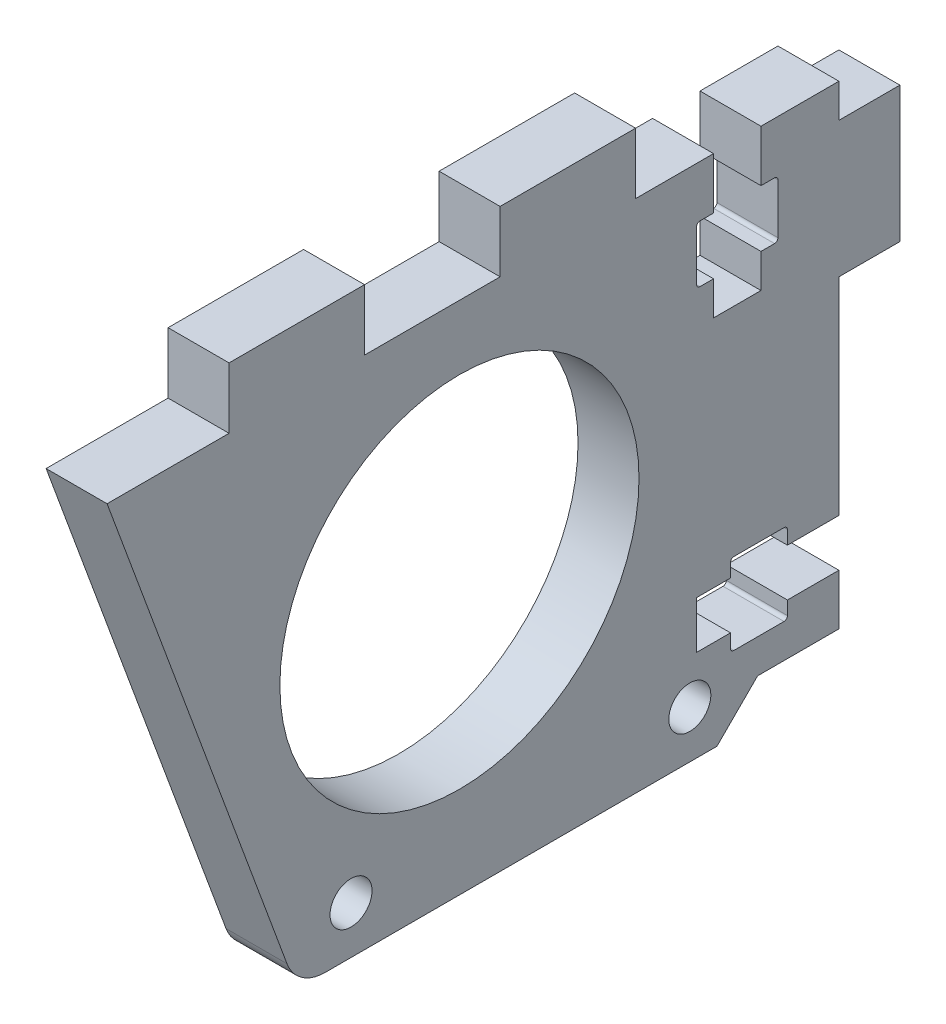
SolidWorks part; units mm, degrees
ref_plane "Front Plane" through (0, 0, 0) normal (0, 0, 1) x (1, 0, 0)
ref_plane "Top Plane" through (0, 0, 0) normal (0, 1, 0) x (1, 0, 0)
ref_plane "Right Plane" through (0, 0, 0) normal (1, 0, 0) x (0, 0, -1)
sketch "Sketch1" plane through (0, 0, 0) normal (1, 0, 0) x (0, 0, -1)
  line L0 (0, 0) -> (0, -35)
  line L1 (0, -35) -> (-54, 0)
  line L2 (-54, 0) -> (0, 0)
  dimension "D1" = 35
  dimension "D2" = 54
extrude "Boss-Extrude1" add sketch "Sketch1" along normal blind 4.5
sketch "Sketch2" plane through (4.5, 0, 0) normal (1, 0, 0) x (0, 0, -1)
  line L0 (0, -35) -> (0, 0) construction
  line L1 (-4.5, -2.5) -> (4.5, -2.5)
  line L2 (-4.5, -2.5) -> (-4.5, -12.5)
  line L3 (-4.5, -12.5) -> (4.5, -12.5)
  line L4 (4.5, -2.5) -> (4.5, -12.5)
  line L5 (-4.5, -2.5) -> (4.5, -12.5) construction
  line L6 (-4.5, -12.5) -> (4.5, -2.5) construction
  line L7 (0, 0) -> (-54, 0) construction
  point P0 (0, -7.5)
  dimension "D1" = 10
  dimension "D2" = 7.5
  dimension "D3" = 4.5
extrude "Boss-Extrude2" add sketch "Sketch2" against normal through all
sketch "Sketch3" plane through (4.5, 0, 0) normal (1, 0, 0) x (0, 0, -1)
  line L0 (0, -35) -> (-15, -35)
  line L1 (0, -25) -> (-54, 0)
  line L4 (0, -35) -> (0, -12.5) construction
  line L5 (0, -25) -> (0, -35)
  line L6 (-54, 0) -> (-15, -35)
  dimension "D1" = 15
  dimension "D2" = 10
extrude "Boss-Extrude3" add sketch "Sketch3" against normal through all
sketch "Sketch4" plane through (4.5, 0, 0) normal (1, 0, 0) x (0, 0, -1)
  line L0 (0, -29.5) -> (-10.5, -29.5) construction
  line L1 (0, -35) -> (0, -12.5) construction
  line L2 (0, -27.75) -> (-10.5, -27.75) construction
  line L3 (-10.5, -27.75) -> (-10.5, -31.25) construction
  line L4 (0, -31.25) -> (0, -27.75)
  line L5 (0, -27.75) -> (-3.8, -27.75)
  line L6 (-3.8, -27.75) -> (-3.8, -26.75)
  line L7 (-4.05, -26.5) -> (-7.75, -26.5)
  line L8 (-8, -26.75) -> (-8, -27.75)
  line L9 (-8, -27.75) -> (-10.5, -27.75)
  line L10 (-10.5, -27.75) -> (-10.5, -31.25)
  line L12 (0, -31.25) -> (-10.5, -31.25) construction
  line L13 (-8, -31.25) -> (-10.5, -31.25)
  line L14 (-8, -32.25) -> (-8, -31.25)
  line L15 (-4.05, -32.5) -> (-7.75, -32.5)
  line L16 (-3.8, -31.25) -> (-3.8, -32.25)
  line L17 (0, -31.25) -> (-3.8, -31.25)
  line L18 (4.5, -12.5) -> (4.5, -2.5) construction
  line L19 (0, -18.5) -> (-33.3857, -18.5) construction
  line L20 (-54, 0) -> (-15, -35) construction
  line L37 (0, -31.25) -> (-10.5, -31.25) construction
  arc A0 (-8, -32.25) -> (-7.75, -32.5) centre (-7.75, -32.25) ccw
  arc A1 (-4.05, -32.5) -> (-3.8, -32.25) centre (-4.05, -32.25) ccw
  arc A2 (-3.8, -26.75) -> (-4.05, -26.5) centre (-4.05, -26.75) ccw
  arc A3 (-7.75, -26.5) -> (-8, -26.75) centre (-7.75, -26.75) ccw
  point P10 (4.5, -7.5)
  point P20 (-8, -32.5)
  point P23 (-3.8, -32.5)
  point P26 (-3.8, -26.5)
  point P29 (-8, -26.5)
  dimension "D7" = 0.25
  dimension "D1" = 10.5
  dimension "D2" = 1.75
  dimension "D3" = 3
  dimension "D4" = 4.2
  dimension "D5" = 8
  dimension "D6" = 22
extrude "Cut-Extrude1" cut sketch "Sketch4" against normal through all
sketch "Sketch5" plane through (4.5, 0, 0) normal (1, 0, 0) x (0, 0, -1)
  line L0 (0, 0) -> (-54, 0) construction
  line L1 (-25, 4.5) -> (-15, 4.5)
  line L2 (-25, 4.5) -> (-25, 0)
  line L3 (0, 0) -> (-54, 0) construction
  line L4 (-15, 4.5) -> (-15, 0)
  line L5 (-25, 4.5) -> (-20, 0) construction
  line L6 (-20, 0) -> (-15, 4.5) construction
  line L7 (-30, 0) -> (-30, 4.5) construction
  line L8 (-40, 0) -> (-45, 4.5) construction
  line L9 (-35, 4.5) -> (-40, 0) construction
  line L10 (-45, 4.5) -> (-45, 0)
  line L12 (-35, 4.5) -> (-35, 0)
  line L13 (-35, 4.5) -> (-45, 4.5)
  line L14 (-20, 0) -> (-15, 4.5) construction
  line L15 (-15, 0) -> (-25, 0)
  line L16 (-35, 0) -> (-45, 0)
  point P0 (-20, 0)
  point P14 (-40, 0)
  dimension "D3" = 4.5
  dimension "D1" = 20
  dimension "D2" = 10
  dimension "D4" = 20
  dimension "D5" = 5
extrude "Boss-Extrude4" add sketch "Sketch5" against normal through all
sketch "Sketch8" [suppressed] plane through (4.5, 0, 0) normal (1, 0, 0) x (0, 0, -1)
  line L0 (-15, -30) -> (-27, -30) construction
  line L1 (-15, -35) -> (-27, -35)
  line L2 (-15, -25) -> (-27, -25)
  line L3 (-15, -35) -> (0, -35) construction
  line L4 (-15, -25) -> (-15, -35)
  arc A1 (-27, -25) -> (-27, -35) centre (-27, -30) ccw
  dimension "D5" = 5
  dimension "D1" = 0
  dimension "D2" = 12
  dimension "D3" = 0
  dimension "D4" = 10
extrude "Boss-Extrude5" [suppressed] add sketch "Sketch8" against normal up to surface (4.5 mm away)
sketch "Sketch9" [suppressed] plane through (4.5, 0, 0) normal (1, 0, 0) x (0, 0, -1)
  line L0 (-27, -30) -> (-22, -30) construction
  line L1 (-27, -27) -> (-22, -27)
  line L2 (-27, -33) -> (-22, -33)
  arc A0 (-27, -27) -> (-27, -33) centre (-27, -30) ccw
  arc A1 (-22, -33) -> (-22, -27) centre (-22, -30) ccw
  point P3 (-24.5, -30)
  dimension "D1" = 3
  dimension "D2" = 5
extrude "Cut-Extrude3" [suppressed] cut sketch "Sketch9" against normal through all
sketch "Sketch10" plane through (0, 0, 0) normal (-1, 0, 0) x (0, 0, 1)
  line L0 (15, -35) -> (54, -12)
  line L1 (54, -12) -> (54, 0)
  line L3 (54, 0) -> (15, -35)
  dimension "D1" = 12
extrude "Boss-Extrude6" [suppressed] add sketch "Sketch10" against normal through all
sketch "Sketch6" plane through (4.5, 0, 0) normal (1, 0, 0) x (0, 0, -1)
  line L0 (-30, 0) -> (-30, -10.5) construction
  line L1 (-25, 0) -> (-35, 0) construction
  line L2 (-28.25, -10.5) -> (-31.75, -10.5) construction
  line L3 (-31.75, -10.5) -> (-31.75, 0) construction
  line L4 (-28.25, 0) -> (-31.75, 0)
  line L5 (-31.75, 0) -> (-31.75, -3.8)
  line L6 (-31.75, -3.8) -> (-32.75, -3.8)
  line L7 (-33, -4.05) -> (-33, -7.75)
  line L8 (-32.75, -8) -> (-31.75, -8)
  line L9 (-31.75, -8) -> (-31.75, -10.5)
  line L10 (-31.75, -10.5) -> (-28.25, -10.5)
  line L11 (-28.25, -10.5) -> (-28.25, 0) construction
  line L12 (-28.25, -8) -> (-28.25, -10.5)
  line L13 (-27.25, -8) -> (-28.25, -8)
  line L14 (-27, -4.05) -> (-27, -7.75)
  line L15 (-28.25, -3.8) -> (-27.25, -3.8)
  line L16 (-28.25, 0) -> (-28.25, -3.8)
  arc A0 (-33, -7.75) -> (-32.75, -8) centre (-32.75, -7.75) ccw
  arc A1 (-32.75, -3.8) -> (-33, -4.05) centre (-32.75, -4.05) ccw
  arc A2 (-27.25, -3.8) -> (-27, -4.05) centre (-27.25, -4.05) cw
  arc A3 (-27, -7.75) -> (-27.25, -8) centre (-27.25, -7.75) cw
  point P12 (-33, -8)
  point P15 (-33, -3.8)
  point P26 (-27, -3.8)
  point P27 (-27, -8)
  dimension "D1" = 10.5
  dimension "D2" = 1.75
  dimension "D4" = 4.2
  dimension "D6" = 0.25
  dimension "D3" = 8
  dimension "D5" = 3
extrude "Cut-Extrude2" [suppressed] cut sketch "Sketch6" against normal through all
sketch "Sketch11" plane through (0, 0, 0) normal (-1, 0, 0) x (0, 0, 1)
  line L0 (7.5, 0) -> (7.5, -10.5) construction
  line L1 (0, 0) -> (15, 0) construction
  line L2 (5.75, -10.5) -> (9.25, -10.5)
  line L3 (9.25, -10.5) -> (9.25, -8)
  line L4 (9.25, -8) -> (10.25, -8)
  line L5 (10.5, -7.75) -> (10.5, -4.05)
  line L6 (10.25, -3.8) -> (9.25, -3.8)
  line L7 (9.25, -3.8) -> (9.25, 0)
  line L8 (9.25, 0) -> (5.75, 0)
  line L9 (9.25, -8) -> (9.25, -3.8) construction
  line L10 (0, 0) -> (15, 0) construction
  line L11 (5.75, -8) -> (5.75, -3.8) construction
  line L12 (5.75, -3.8) -> (5.75, 0)
  line L13 (4.75, -3.8) -> (5.75, -3.8)
  line L14 (4.5, -7.75) -> (4.5, -4.05)
  line L15 (5.75, -8) -> (4.75, -8)
  line L16 (5.75, -10.5) -> (5.75, -8)
  arc A0 (10.5, -4.05) -> (10.25, -3.8) centre (10.25, -4.05) ccw
  arc A1 (4.75, -3.8) -> (4.5, -4.05) centre (4.75, -4.05) ccw
  arc A2 (10.25, -8) -> (10.5, -7.75) centre (10.25, -7.75) ccw
  arc A3 (4.5, -7.75) -> (4.75, -8) centre (4.75, -7.75) ccw
  point P11 (7.5, 0)
  point P22 (10.5, -3.8)
  point P25 (4.5, -3.8)
  point P28 (10.5, -8)
  point P31 (4.5, -8)
  dimension "D7" = 0.25
  dimension "D1" = 10.5
  dimension "D3" = 3
  dimension "D8" = 0.25
  dimension "D2" = 4.2
  dimension "D4" = 8
  dimension "D5" = 1.75
  dimension "D6" = 0
extrude "Cut-Extrude4" cut sketch "Sketch11" against normal through all
sketch "Sketch12" plane through (0, 0, 0) normal (-1, 0, 0) x (0, 0, 1)
  line L0 (28, -18) -> (16, -6) construction
  line L1 (28, -18) -> (28, -4.75) construction
  line L2 (28, -18) -> (40, -6) construction
  line L3 (28, -18) -> (14.75, -18) construction
  line L4 (28, -18) -> (16, -30) construction
  line L5 (28, -18) -> (16, -6) construction
  line L6 (0, -27.75) -> (0, -12.5) construction
  line L7 (25, 0) -> (35, 0) construction
  circle A0 centre (28, -18) radius 13.25
  circle A1 centre (16, -6) radius 1.55
  circle A2 centre (40, -6) radius 1.55
  circle A3 centre (16, -30) radius 1.55
  dimension "D1" = 26.5
  dimension "D2" = 3.1
  dimension "D3" = 12
  dimension "D4" = 45
  dimension "D5" = 28
  dimension "D6" = 18
extrude "Cut-Extrude5" [suppressed] cut sketch "Sketch12" against normal through all
sketch "Sketch13" [suppressed] plane through (0, 0, 0) normal (-1, 0, 0) x (0, 0, 1)
  line L0 (38.894, -10.458) -> (43.005, -7.6119)
  line L1 (19.9513, -28.5252) -> (16.914, -32.497)
  line L6 (28, -18) -> (54, 0) construction
  line L7 (28, -18) -> (15, -35) construction
  arc A0 (19.9513, -28.5252) -> (38.894, -10.458) centre (28, -18) ccw
  arc A1 (16.914, -32.497) -> (43.005, -7.6119) centre (28, -18) ccw
  arc A3 (40.0595, -12.5107) -> (21.2428, -29.3975) centre (28, -18) ccw construction
  dimension "D1" = 5
extrude "Boss-Extrude7" [suppressed] add sketch "Sketch13" against normal through all
sketch "Sketch14" [suppressed] plane through (0, 0, 0) normal (-1, 0, 0) x (0, 0, 1)
  line L0 (28, -4.75) -> (28, -31.25) construction
  line L1 (28, -18) -> (40, -30) construction
  circle A0 centre (28, -18) radius 13.25 construction
  circle A1 centre (40, -30) radius 3.5
  dimension "D2" = 7
  dimension "D1" = 45
  dimension "D3" = 12
extrude "Boss-Extrude8" [suppressed] add sketch "Sketch14" against normal through all
sketch "Sketch15" [suppressed] plane through (0, 0, 0) normal (-1, 0, 0) x (0, 0, 1)
  line L0 (42.4749, -32.4749) -> (28, -18) construction
  arc A0 (38.305, -33.0622) -> (43.0622, -28.305) centre (40, -30) ccw construction
  circle A1 centre (40, -30) radius 1.55
  dimension "D1" = 3.1
extrude "Cut-Extrude6" [suppressed] cut sketch "Sketch15" against normal through all
sketch "Sketch16" plane through (4.5, 0, 0) normal (1, 0, 0) x (0, 0, -1)
  line L0 (0, -34.5) -> (-39, -34.5) construction
  line L1 (0, -27.75) -> (0, -12.5) construction
  line L2 (-15, -34.5) -> (-39, -34.5) construction
  line L3 (-15, -38.5) -> (-39, -38.5)
  line L4 (-15, -30.5) -> (-39, -30.5)
  arc A0 (-15, -38.5) -> (-15, -30.5) centre (-15, -34.5) ccw
  arc A1 (-39, -30.5) -> (-39, -38.5) centre (-39, -34.5) ccw
  point P5 (-27, -34.5)
  point P12 (0, -20.125)
  dimension "D1" = 4
  dimension "D2" = 34.5
  dimension "D3" = 39
  dimension "D4" = 15
extrude "Boss-Extrude9" [suppressed] add sketch "Sketch16" against normal through all
sketch "Sketch17" [suppressed] plane through (4.5, 0, 0) normal (1, 0, 0) x (0, 0, -1)
  line L0 (-43, -34.5) -> (0, -34.5) construction
  line L1 (0, -27.75) -> (0, -12.5) construction
  line L2 (-26.5, -34.5) -> (-26.5, -20.0064) construction
  arc A0 (-42.1823, -32.0766) -> (-39, -38.5) centre (-39, -34.5) ccw construction
  circle A1 centre (-39, -34.5) radius 1.55
  circle A2 centre (-14, -34.5) radius 1.55
  dimension "D1" = 3.1
  dimension "D2" = 12.5
extrude "Cut-Extrude7" [suppressed] cut sketch "Sketch17" against normal through all
sketch "Sketch18" [suppressed] plane through (4.5, 0, 0) normal (1, 0, 0) x (0, 0, -1)
  line L0 (-15, -38.5) -> (0, -35)
  line L1 (0, -35) -> (-11.0314, -35)
  line L2 (-11.0314, -35) -> (-15, -38.5)
extrude "Boss-Extrude10" [suppressed] add sketch "Sketch18" against normal through all
sketch "Sketch20" plane through (4.5, 0, 0) normal (1, 0, 0) x (0, 0, -1)
  line L0 (0, -35) -> (0, -31.25) construction
  line L1 (-9, -38) -> (-37.9081, -38)
  line L2 (-40.7232, -36.0371) -> (-54, 0)
  line L3 (-54, 0) -> (-15, -35)
  line L4 (-15, -35) -> (-6, -35)
  line L5 (-9, -38) -> (-6, -35)
  line L6 (-40.7232, -36.0371) -> (-40, -38) construction
  line L7 (-40, -38) -> (-37.9081, -38) construction
  arc A1 (-37.9081, -38) -> (-40.7232, -36.0371) centre (-37.9081, -35) cw
  point P0 (0, -33.125)
  point P14 (-40, -38)
  dimension "D3" = 6
  dimension "D4" = 3
  dimension "D1" = 40
  dimension "D2" = 3
  dimension "D5" = 135
extrude "Boss-Extrude11" add sketch "Sketch20" against normal through all
sketch "Sketch21" plane through (4.5, 0, 0) normal (1, 0, 0) x (0, 0, -1)
  line L0 (0, -34.5) -> (-41.2895, -34.5) construction
  line L1 (0, -35) -> (0, -31.25) construction
  line L2 (-54, 0) -> (-40.7232, -36.0371) construction
  line L3 (0, -27.75) -> (0, -12.5) construction
  circle A0 centre (-36, -34.5) radius 1.55
  circle A1 centre (-11, -34.5) radius 1.55
  dimension "D2" = 3.1
  dimension "D3" = 3.1
  dimension "D1" = 25
  dimension "D4" = 34.5
  dimension "D5" = 11
extrude "Cut-Extrude8" cut sketch "Sketch21" against normal through all
sketch "Sketch22" plane through (4.5, 0, 0) normal (1, 0, 0) x (0, 0, -1)
  line L0 (0, -27.75) -> (0, -12.5) construction
  line L1 (-25, 0) -> (-35, 0) construction
  circle A0 centre (-28, -18) radius 13.25
  dimension "D2" = 18
  dimension "D3" = 26.5
  dimension "D1" = 28
extrude "Cut-Extrude9" cut sketch "Sketch22" against normal through all
equation "\"X-ROD-SPACING\"=45"
equation "\"Y-ROD-SPACING\"=75"
equation "\"Z-ROD-SPACING\"=17.5"
equation "\"Y-BED-OFFSET\"=2"
equation "\"Y-BED-ROD-INSET\"=3.5"
equation "\"Y-BED-SCREW-SPACING\"=209"
equation "\"Y-BED-SCREW-CUTOUT-SLOT-HEIGHT\"=2"
equation "\"T-SLOT-NUT-FILLET-RADIUS\"=0.25"
equation "\"T-SLOT-SCREW-SHAFT-RADIUS\"=1.75"
equation "\"T-SLOT-SCREW-SHAFT-CUTOUT-LENGTH\"=10.5"
equation "\"T-SLOT-NUT-DEPTH\"=4.2"
equation "\"T-SLOT-NUT-WIDTH\"=3"
equation "\"T-SLOT-NUT-END-DISTANCE\"=8"
equation "\"ACRYLIC-THICKNESS\"=10"
equation "\"ACRYLIC-THICKNESS2\"=4.5"
equation "\"ACRYLIC-TAB-CUTOUT-SIZE\"=\"ACRYLIC-THICKNESS\"+\"ACRYLIC-TAB-TOLERANCE\"*2"
equation "\"ACRYLIC-TAB-WIDTH\"=\"ACRYLIC-THICKNESS\""
equation "\"ACRYLIC-M3-HOLE\"=3.1"
equation "\"SMOOTHROD-CAP-SCREW-DISTANCE\"=20"
equation "\"FRAME-WIDTH-INNER\"=370"
equation "\"NEMA17-HOLE-SPACING\"=31"
equation "\"NEMA17-CENTRAL-CUTOUT\"=22.5"
equation "\"Z-BRACKET-REACH\"=55"
equation "\"Z-ROD-INSET\"=16"
equation "\"TOP-BRACKET-SPACING\"=40"
equation "\"SMOOTHROD-X-LENGTH\"=350"
equation "\"SMOOTHROD-Y-LENGTH\"=350"
equation "\"SMOOTHROD-Z-LENGTH\"=350"
equation "\"SMOOTHROD-TIGHTENING-HEADROOM\"=.25"
equation "\"LEADSCREW-Z-LENGTH\"=300"
equation "\"SCREW-LENGTH-FRAME\"=\"ACRYLIC-THICKNESS\" + 10"
equation "\"SCREW-LENGTH-MOTOR\"=\"ACRYLIC-THICKNESS\" + 5"
equation "\"SCREW-LENGTH-EXTRUDER\"=28"
equation "\"SCREW-HEAD-RADIUS\"=6"
equation "\"PRINTED-X-SMOOTHROD-DIAMETER\"=8.2"
equation "\"PRINTED-X-SMOOTHROD-CUTOUT\"=10"
equation "\"PRINTED-X-BASE-HEIGHT\"=10"
equation "\"PRINTED-LM8UU-CUTOUT-SIZE\"=15.25"
equation "\"PRINTED-LM8UU-CUTOUT-LENGTH\"=24.5"
equation "\"PRINTED-X-IDLER-HEIGHT\"=16"
equation "\"PSU-MOUNTING-WIDTH\"=95"
equation "\"PSU-MOUNTING-HEIGHT\"=177"
equation "\"Y-BELT-TO-ROD-DISTANCE\"=20"
equation "\"SPOOL-HOLDER-ROD-SPACING\"=150"
equation "\"ACRYLIC-X-CARRIAGE-WIDTH\"=55"
equation "\"ACRYLIC-X-CARRIAGE-HEIGHT\"=75"
equation "\"ACRYLIC-X-CARRIAGE-SCREW-SPACING-X\"=15"
equation "\"ACRYLIC-X-CARRIAGE-SCREW-SPACING-Y\"=33"
equation "\"ACRYLIC-X-CARRIAGE-CENTER-TAB-SPACING\"=14"
equation "\"ACRYLIC-X-CARRIAGE-EXTRUDER-SHELF-DEPTH\"=\"ACRYLIC-X-CARRIAGE-EXTRUDER-OFFSET\" + 28"
equation "\"D2@Sketch1\"=\"ACRYLIC-X-CARRIAGE-EXTRUDER-SHELF-DEPTH\""
equation "\"D1@Boss-Extrude1\"=\"ACRYLIC-THICKNESS2\""
equation "\"D1@Sketch2\"=\"ACRYLIC-TAB-WIDTH\""
equation "\"D3@Sketch2\"=\"ACRYLIC-THICKNESS2\""
equation "\"ACRYLIC-X-CARRIAGE-LM8UU-CUTOUT-WIDTH\"=24.25"
equation "\"ACRYLIC-X-CARRIAGE-EXTRUDER-BRACE-SPACING\"=23"
equation "\"ACRYLIC-X-CARRIAGE-EXTRUDER-BRACE-HEIGHT\"=35"
equation "\"D1@Sketch1\"=\"ACRYLIC-X-CARRIAGE-EXTRUDER-BRACE-HEIGHT\""
equation "\"D1@Sketch4\"=\"T-SLOT-SCREW-SHAFT-CUTOUT-LENGTH\""
equation "\"D2@Sketch4\"=\"T-SLOT-SCREW-SHAFT-RADIUS\""
equation "\"D3@Sketch4\"=\"T-SLOT-NUT-WIDTH\""
equation "\"D4@Sketch4\"=\"T-SLOT-NUT-DEPTH\""
equation "\"D5@Sketch4\"=\"T-SLOT-NUT-END-DISTANCE\""
equation "\"D7@Sketch4\"=\"T-SLOT-NUT-FILLET-RADIUS\""
equation "\"ACRYLIC-X-CARRIAGE-EXTRUDER-BRACE-SCREW-SPACING\"=22"
equation "\"D6@Sketch4\"=\"ACRYLIC-X-CARRIAGE-EXTRUDER-BRACE-SCREW-SPACING\""
equation "\"ACRYLIC-X-CARRIAGE-EXTRUDER-BRACE-TAB-OFFSET\"=20"
equation "\"D1@Sketch5\"=\"ACRYLIC-X-CARRIAGE-EXTRUDER-BRACE-TAB-OFFSET\""
equation "\"D2@Sketch5\"=\"ACRYLIC-TAB-WIDTH\""
equation "\"D3@Sketch5\"=\"ACRYLIC-THICKNESS2\""
equation "\"ACRYLIC-X-CARRIAGE-EXTRUDER-OFFSET\"=26"
equation "\"ACRYLIC-X-CARRIAGE-EXTRUDER-ANGLE\"=90"
equation "\"D1@Sketch6\"=\"T-SLOT-SCREW-SHAFT-CUTOUT-LENGTH\""
equation "\"D2@Sketch6\"=\"T-SLOT-SCREW-SHAFT-RADIUS\""
equation "\"D3@Sketch6\"=\"T-SLOT-NUT-END-DISTANCE\""
equation "\"D4@Sketch6\"=\"T-SLOT-NUT-DEPTH\""
equation "\"D5@Sketch6\"=\"T-SLOT-NUT-WIDTH\""
equation "\"D6@Sketch6\"=\"T-SLOT-NUT-FILLET-RADIUS\""
equation "\"D1@Sketch11\"=\"T-SLOT-SCREW-SHAFT-CUTOUT-LENGTH\""
equation "\"D2@Sketch11\"=\"T-SLOT-NUT-DEPTH\""
equation "\"D3@Sketch11\"=\"T-SLOT-NUT-WIDTH\""
equation "\"D4@Sketch11\"=\"T-SLOT-NUT-END-DISTANCE\""
equation "\"D5@Sketch11\"=\"T-SLOT-SCREW-SHAFT-RADIUS\""
equation "\"D7@Sketch11\"=\"T-SLOT-NUT-FILLET-RADIUS\""
equation "\"D8@Sketch11\"=\"T-SLOT-NUT-FILLET-RADIUS\""
equation "\"D2@Sketch12\"=\"ACRYLIC-M3-HOLE\""
equation "\"D1@Sketch15\"=\"ACRYLIC-M3-HOLE\""
equation "\"D1@Sketch17\"=\"ACRYLIC-M3-HOLE\""
equation "\"D2@Sketch21\"=\"ACRYLIC-M3-HOLE\""
equation "\"D3@Sketch21\"=\"ACRYLIC-M3-HOLE\""
